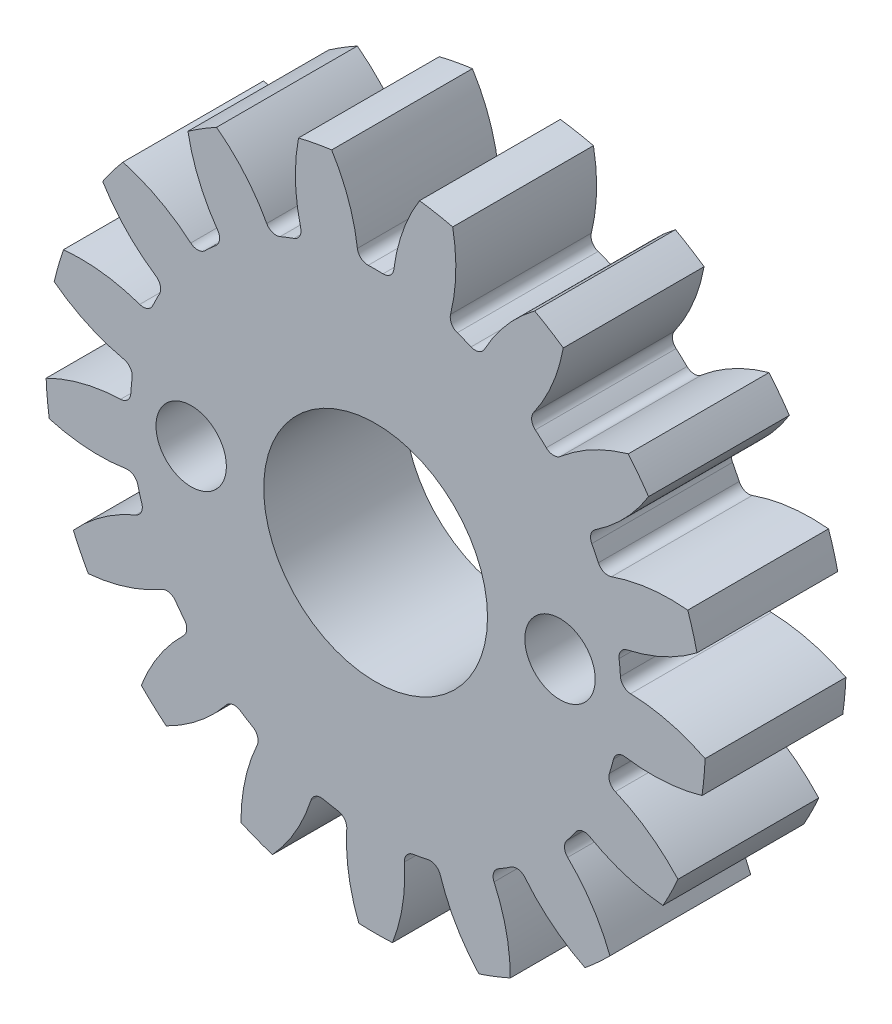
SolidWorks part; units mm, degrees
other "Markup1"
sketch "Sketch7" plane through (4.681, 4.6432, -1) normal (0.0832, 0.0094, -0.9965) x (-0.9203, -0.3829, -0.0804)
ref_plane "Front Plane" through (0, 0, 0) normal (0, 0, 1) x (1, 0, 0)
ref_plane "Top Plane" through (0, 0, 0) normal (0, 1, 0) x (1, 0, 0)
ref_plane "Right Plane" through (0, 0, 0) normal (1, 0, 0) x (0, 0, -1)
sketch "Sketch1" plane through (0, 0, 0) normal (0, 0, 1) x (1, 0, 0)
  circle A0 centre (0, 0) radius 4.185 construction
  circle A1 centre (0, 0) radius 4.685
  dimension "D1" = 8.37
  dimension "D2" = 9.37
extrude "Boss-Extrude1" add sketch "Sketch1" along normal mid plane 2
sketch "Sketch3" plane through (0, 0, 0) normal (0, 0, 1) x (1, 0, 0)
  line L0 (0, 4.685) -> (0, 0) construction
  line L1 (0, 0) -> (1.7175, 4.3588) construction
  line L2 (0, 0) -> (0.8741, 4.6027) construction
  line L3 (-0.2452, 3.4764) -> (0, 0) construction
  line L4 (-0.3921, 4.1666) -> (0.3921, 4.1666) construction
  line L5 (0.3921, 4.1666) -> (1.1626, 4.0203) construction
  line L6 (-0.5682, 4.6504) -> (0, 3.0892) construction
  circle A0 centre (0, 0) radius 3.685 construction
  arc A1 (0.2452, 3.4764) -> (-0.2452, 3.4764) centre (0, 0) ccw
  circle A2 centre (0, 0) radius 4.685 construction
  arc A3 (-0.6245, 4.6432) -> (-0.2452, 3.4764) centre (-2.7796, 3.2976) cw
  circle A5 centre (0, 0) radius 4.685 construction
  arc A6 (0.6245, 4.6432) -> (0.2452, 3.4764) centre (2.7796, 3.2976) ccw
  circle A7 centre (0, 0) radius 4.185 construction
  arc A9 (0.6245, 4.6432) -> (-0.6245, 4.6432) centre (0, 0) ccw
  dimension "D1" = 21.505
  dimension "D2" = 1
  dimension "D3" = 1.2
  dimension "D4" = 0.2
  dimension "D5" = 20
extrude "Cut-Extrude1" cut sketch "Sketch3" against normal through all both and the other way through all
fillet "Fillet1" radius 0.15 2 edges at (-0.2452, 3.4764, 0) (0.2452, 3.4764, 0)
pattern_circular "CirPattern1" count 17 over 360 about axis through (0, 0, 0) along (0, 0, 1) of "Fillet1", "Cut-Extrude1"
sketch "Sketch6" plane through (0, 0, 1) normal (0, 0, 1) x (1, 0, 0)
  line L0 (0, -1.1) -> (0, 1.1) construction
  circle A0 centre (-2.6201, 0) radius 0.5
  circle A1 centre (2.6201, 0) radius 0.5
  dimension "D1" = 1
extrude "Cut-Extrude3" cut sketch "Sketch6" against normal through all
sketch "Sketch8" plane through (0, 0, 1) normal (0, 0, 1) x (1, 0, 0)
  circle A0 centre (0, 0) radius 1.59
extrude "Cut-Extrude4" cut sketch "Sketch8" against normal blind 10
equation "\"module\"= 0.5mm"
equation "\"number of teeth\"= 16.74"
equation "\"pressure angle\"= 20"
equation "\"D1@Sketch1\"= \"module\" * \"number of teeth\""
equation "\"D2@Sketch1\"=(\"number of teeth\" + 2) * \"module\" "
equation "\"D1@Sketch3\"=360 / \"number of teeth\""
equation "\"D3@Sketch3\"= \"module\"  * if( \"module\" => 1.25,2.25,2.4)"
equation "\"D5@Sketch3\"=\"pressure angle\""
equation "\"D1@Fillet1\"=0.3 * \"module\""
equation "\"D1@CirPattern1\"=\"number of teeth\""
equation "\"D1@Chamfer1\"=\"module\""
